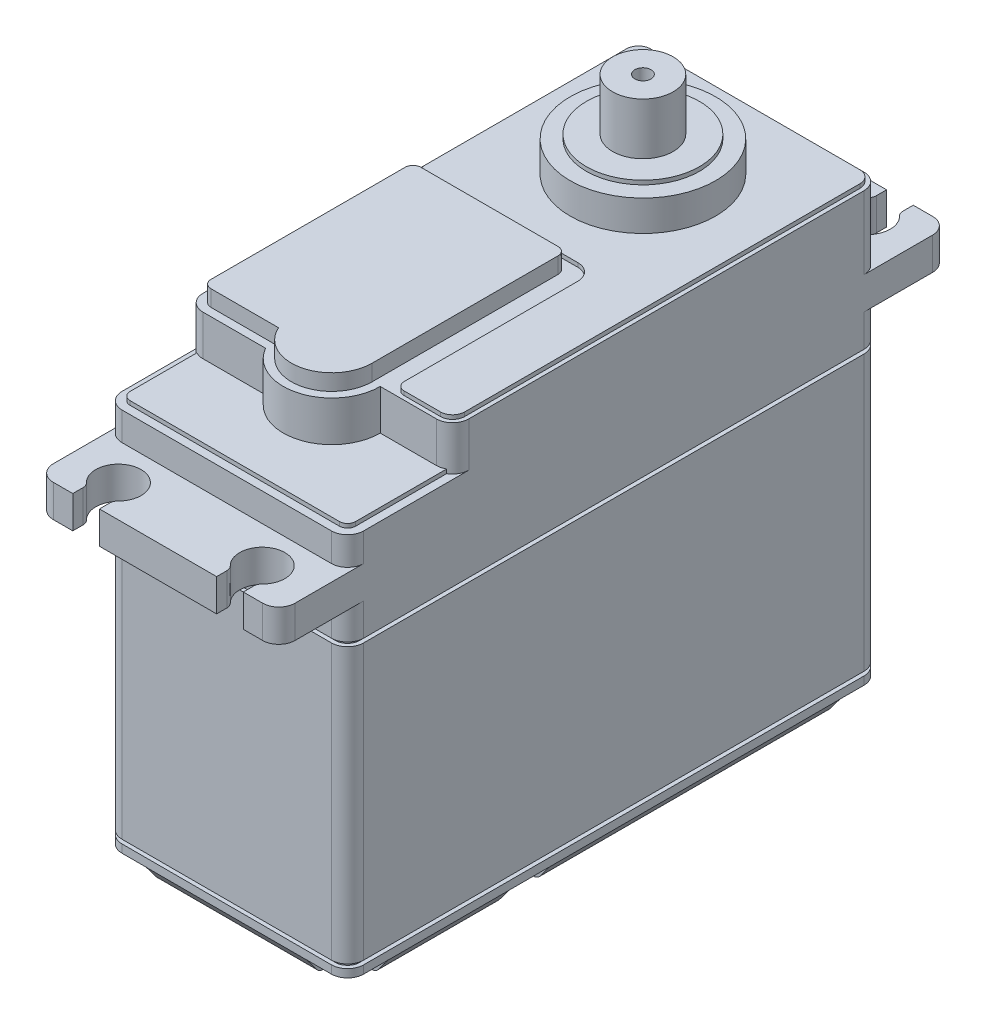
SolidWorks part; units mm, degrees
ref_plane "Front Plane" through (0, 0, 0) normal (0, 0, 1) x (1, 0, 0)
ref_plane "Top Plane" through (0, 0, 0) normal (0, 1, 0) x (1, 0, 0)
ref_plane "Right Plane" through (0, 0, 0) normal (1, 0, 0) x (0, 0, -1)
sketch "Sketch1" plane through (0, 0, 0) normal (0, 1, 0) x (1, 0, 0)
  line L1 (12.95, 32.95) -> (-12.95, 32.95)
  line L2 (14.95, 30.95) -> (14.95, -30.95)
  line L3 (12.95, -32.95) -> (-12.95, -32.95)
  line L4 (-14.95, 30.95) -> (-14.95, -30.95)
  line L5 (14.95, 32.95) -> (-14.95, -32.95) construction
  line L6 (14.95, -32.95) -> (-14.95, 32.95) construction
  arc A0 (-12.95, 32.95) -> (-14.95, 30.95) centre (-12.95, 30.95) ccw
  arc A1 (12.95, 32.95) -> (14.95, 30.95) centre (12.95, 30.95) cw
  arc A2 (-12.95, -32.95) -> (-14.95, -30.95) centre (-12.95, -30.95) cw
  arc A3 (12.95, -32.95) -> (14.95, -30.95) centre (12.95, -30.95) ccw
  point P0 (0, 0)
  dimension "D3" = 2
  dimension "D1" = 29.9
  dimension "D2" = 65.9
extrude "Boss-Extrude1" add sketch "Sketch1" along normal blind 42
sketch "Sketch2" plane through (0, 0, 0) normal (0, -1, 0) x (1, 0, 0)
  line L0 (-14.95, -27.95) -> (-14.95, -32.95)
  line L2 (-14.95, -32.95) -> (-9.95, -32.95)
  line L4 (-14.95, -27.95) -> (-12.45, -27.95)
  line L5 (-9.95, -30.45) -> (-9.95, -32.95)
  line L6 (14.95, 30.95) -> (14.95, -30.95) construction
  line L7 (-14.95, -30.95) -> (-14.95, 30.95) construction
  line L8 (9.95, -30.45) -> (9.95, -32.95)
  line L9 (14.95, -27.95) -> (12.45, -27.95)
  line L10 (14.95, -32.95) -> (9.95, -32.95)
  line L11 (14.95, -27.95) -> (14.95, -32.95)
  line L12 (14.95, 27.95) -> (14.95, 32.95)
  line L13 (14.95, 32.95) -> (9.95, 32.95)
  line L14 (14.95, 27.95) -> (12.45, 27.95)
  line L15 (9.95, 30.45) -> (9.95, 32.95)
  line L16 (-9.95, 30.45) -> (-9.95, 32.95)
  line L17 (-14.95, 27.95) -> (-12.45, 27.95)
  line L18 (-14.95, 32.95) -> (-9.95, 32.95)
  line L19 (-14.95, 27.95) -> (-14.95, 32.95)
  line L20 (-12.95, 32.95) -> (12.95, 32.95) construction
  line L21 (-12.45, -5.45) -> (-14.95, -5.45)
  line L22 (-14.95, -5.45) -> (-14.95, -10.45)
  line L23 (-14.95, -10.45) -> (-12.45, -10.45)
  line L24 (12.45, 7.95) -> (14.95, 7.95)
  line L25 (14.95, 7.95) -> (14.95, 12.95)
  line L26 (14.95, 12.95) -> (12.45, 12.95)
  arc A0 (-9.95, -30.45) -> (-12.45, -27.95) centre (-12.45, -30.45) ccw
  arc A1 (9.95, -30.45) -> (12.45, -27.95) centre (12.45, -30.45) cw
  arc A2 (9.95, 30.45) -> (12.45, 27.95) centre (12.45, 30.45) ccw
  arc A3 (-9.95, 30.45) -> (-12.45, 27.95) centre (-12.45, 30.45) cw
  arc A4 (12.45, 12.95) -> (12.45, 7.95) centre (12.45, 10.45) ccw
  arc A5 (-12.45, -10.45) -> (-12.45, -5.45) centre (-12.45, -7.95) ccw
  point P7 (-9.95, -32.95)
  point P8 (-14.95, -27.95)
  point P10 (14.95, 10.45)
  point P13 (-14.95, -7.95)
  point P18 (14.95, -27.95)
  point P19 (9.95, -32.95)
  point P32 (9.95, 32.95)
  point P33 (14.95, 27.95)
  point P34 (-14.95, 27.95)
  point P35 (-9.95, 32.95)
  dimension "D1" = 5
  dimension "D2" = 5
  dimension "D3" = 25
  dimension "D4" = 22.5
  dimension "D5" = 0
extrude "Cut-Extrude1" cut sketch "Sketch2" against normal blind 2
chamfer "Chamfer1" distance 1.5 angle 53 6 edges at (0, 0, 32.95) (-14.95, 0, 11.25) (-14.95, 0, -19.2) (0, 0, -32.95) (14.95, 0, 20.45) (14.95, 0, -10)
fillet "Fillet1" radius 1 6 edges at (13.45, 0, 20.45) (13.45, 0, -10) (0, 0, -31.45) (-13.45, 0, -19.2) (-13.45, 0, 11.25) (0, 0, 31.45)
sketch "Sketch3" plane through (0, 2, 0) normal (0, -1, 0) x (1, 0, 0)
  circle A0 centre (12.45, 30.45) radius 1.5
  circle A1 centre (12.45, 10.45) radius 1.5
  circle A2 centre (12.45, -30.45) radius 1.5
  circle A3 centre (-12.45, -30.45) radius 1.5
  circle A4 centre (-12.45, -8.1512) radius 1.5
  circle A5 centre (-12.45, 30.45) radius 1.5
extrude "Boss-Extrude2" add sketch "Sketch3" along normal blind 1
fillet "Fillet2" radius 0.3 6 edges at (12.45, 1, 28.95) (12.45, 1, 8.95) (12.45, 1, -31.95) (-12.45, 1, -31.95) (-12.45, 1, -9.6512) (-12.45, 1, 28.95)
sketch "Sketch4" plane through (0, 1, 0) normal (0, -1, 0) x (-1, 0, 0)
  line L0 (-12.1, -10.2) -> (-11.1743, -10.2)
  line L1 (-12.1, -30.2) -> (-11.1743, -30.2)
  line L2 (-12.7, -31.7257) -> (-12.7, -30.8)
  line L3 (-13.7257, -30.2) -> (-12.8, -30.2)
  line L4 (-12.2, -31.7257) -> (-12.2, -30.8)
  line L5 (-13.7257, -30.7) -> (-12.8, -30.7)
  line L6 (-12.1, -30.7) -> (-11.1743, -30.7)
  line L7 (-12.7, -30.1) -> (-12.7, -29.1743)
  line L9 (-12.2, 30.1) -> (-12.2, 29.1743)
  line L10 (-12.2, -30.1) -> (-12.2, -29.1743)
  line L11 (-12.7, 30.1) -> (-12.7, 29.1743)
  line L12 (-12.1, 30.7) -> (-11.1743, 30.7)
  line L13 (-13.7257, 30.7) -> (-12.8, 30.7)
  line L14 (-12.2, 31.7257) -> (-12.2, 30.8)
  line L15 (-13.7257, 30.2) -> (-12.8, 30.2)
  line L16 (-12.7, 31.7257) -> (-12.7, 30.8)
  line L17 (-12.1, 30.2) -> (-11.1743, 30.2)
  line L18 (12.1, 30.2) -> (11.1743, 30.2)
  line L19 (12.7, 31.7257) -> (12.7, 30.8)
  line L20 (13.7257, 30.2) -> (12.8, 30.2)
  line L21 (12.2, 31.7257) -> (12.2, 30.8)
  line L22 (13.7257, 30.7) -> (12.8, 30.7)
  line L23 (12.1, 30.7) -> (11.1743, 30.7)
  line L24 (12.7, 30.1) -> (12.7, 29.1743)
  line L25 (12.2, -30.1) -> (12.2, -29.1743)
  line L26 (12.2, 30.1) -> (12.2, 29.1743)
  line L27 (12.7, -30.1) -> (12.7, -29.1743)
  line L28 (12.1, -30.7) -> (11.1743, -30.7)
  line L29 (13.7257, -30.7) -> (12.8, -30.7)
  line L30 (12.2, -31.7257) -> (12.2, -30.8)
  line L31 (13.7257, -30.2) -> (12.8, -30.2)
  line L32 (12.7, -31.7257) -> (12.7, -30.8)
  line L33 (12.1, -30.2) -> (11.1743, -30.2)
  line L34 (-12.2, -10.1) -> (-12.2, -9.1743)
  line L35 (11.1743, 7.9012) -> (12.1, 7.9012)
  line L36 (12.2, 8.5012) -> (12.2, 9.4269)
  line L37 (12.7, 6.8754) -> (12.7, 7.8012)
  line L38 (-12.2, -11.7257) -> (-12.2, -10.8)
  line L39 (-13.7257, -10.7) -> (-12.8, -10.7)
  line L40 (11.1743, 8.4012) -> (12.1, 8.4012)
  line L41 (12.2, 6.8754) -> (12.2, 7.8012)
  line L42 (-12.7, -11.7257) -> (-12.7, -10.8)
  line L43 (-13.7257, -10.2) -> (-12.8, -10.2)
  line L44 (-12.7, -10.1) -> (-12.7, -9.1743)
  line L45 (12.8, 7.9012) -> (13.7257, 7.9012)
  line L47 (12.8, 8.4012) -> (13.7257, 8.4012)
  line L48 (12.7, 8.5012) -> (12.7, 9.4269)
  line L51 (-12.1, -10.7) -> (-11.15, -10.7)
  arc A1 (-12.7, -31.7257) -> (-12.2, -31.7257) centre (-12.45, -30.45) ccw
  arc A2 (-13.7257, -30.2) -> (-13.7257, -30.7) centre (-12.45, -30.45) ccw
  arc A3 (-12.2, -29.1743) -> (-12.7, -29.1743) centre (-12.45, -30.45) ccw
  arc A4 (-11.1743, -30.7) -> (-11.1743, -30.2) centre (-12.45, -30.45) ccw
  arc A5 (-12.1, -30.7) -> (-12.2, -30.8) centre (-12.1, -30.8) ccw
  arc A6 (-12.2, -30.1) -> (-12.1, -30.2) centre (-12.1, -30.1) ccw
  arc A7 (-12.8, -30.2) -> (-12.7, -30.1) centre (-12.8, -30.1) ccw
  arc A8 (-12.8, -30.7) -> (-12.7, -30.8) centre (-12.8, -30.8) cw
  arc A9 (-12.8, 30.7) -> (-12.7, 30.8) centre (-12.8, 30.8) ccw
  arc A10 (-12.8, 30.2) -> (-12.7, 30.1) centre (-12.8, 30.1) cw
  arc A11 (-12.2, 30.1) -> (-12.1, 30.2) centre (-12.1, 30.1) cw
  arc A12 (-12.1, 30.7) -> (-12.2, 30.8) centre (-12.1, 30.8) cw
  arc A13 (-11.1743, 30.7) -> (-11.1743, 30.2) centre (-12.45, 30.45) cw
  arc A14 (-12.2, 29.1743) -> (-12.7, 29.1743) centre (-12.45, 30.45) cw
  arc A15 (-13.7257, 30.2) -> (-13.7257, 30.7) centre (-12.45, 30.45) cw
  arc A16 (-12.7, 31.7257) -> (-12.2, 31.7257) centre (-12.45, 30.45) cw
  arc A17 (12.7, 31.7257) -> (12.2, 31.7257) centre (12.45, 30.45) ccw
  arc A18 (13.7257, 30.2) -> (13.7257, 30.7) centre (12.45, 30.45) ccw
  arc A19 (12.2, 29.1743) -> (12.7, 29.1743) centre (12.45, 30.45) ccw
  arc A20 (11.1743, 30.7) -> (11.1743, 30.2) centre (12.45, 30.45) ccw
  arc A21 (12.1, 30.7) -> (12.2, 30.8) centre (12.1, 30.8) ccw
  arc A22 (12.2, 30.1) -> (12.1, 30.2) centre (12.1, 30.1) ccw
  arc A23 (12.8, 30.2) -> (12.7, 30.1) centre (12.8, 30.1) ccw
  arc A24 (12.8, 30.7) -> (12.7, 30.8) centre (12.8, 30.8) cw
  arc A25 (12.8, -30.7) -> (12.7, -30.8) centre (12.8, -30.8) ccw
  arc A26 (12.8, -30.2) -> (12.7, -30.1) centre (12.8, -30.1) cw
  arc A27 (12.2, -30.1) -> (12.1, -30.2) centre (12.1, -30.1) cw
  arc A28 (12.1, -30.7) -> (12.2, -30.8) centre (12.1, -30.8) cw
  arc A29 (11.1743, -30.7) -> (11.1743, -30.2) centre (12.45, -30.45) cw
  arc A30 (12.2, -29.1743) -> (12.7, -29.1743) centre (12.45, -30.45) cw
  arc A31 (13.7257, -30.2) -> (13.7257, -30.7) centre (12.45, -30.45) cw
  arc A32 (12.7, -31.7257) -> (12.2, -31.7257) centre (12.45, -30.45) cw
  arc A33 (-12.7, -11.7257) -> (-12.2, -11.7257) centre (-12.45, -10.45) ccw
  arc A34 (12.2, 6.8754) -> (12.7, 6.8754) centre (12.45, 8.1512) ccw
  arc A35 (-13.7257, -10.2) -> (-13.7257, -10.7) centre (-12.45, -10.45) ccw
  arc A36 (-12.2, -9.1743) -> (-12.7, -9.1743) centre (-12.45, -10.45) ccw
  arc A37 (-11.1743, -10.7) -> (-11.1743, -10.2) centre (-12.45, -10.45) ccw
  arc A38 (-12.7, -10.1) -> (-12.8, -10.2) centre (-12.8, -10.1) cw
  arc A39 (-12.1, -10.2) -> (-12.2, -10.1) centre (-12.1, -10.1) cw
  arc A40 (-12.1, -10.7) -> (-12.2, -10.8) centre (-12.1, -10.8) ccw
  arc A41 (-12.7, -10.8) -> (-12.8, -10.7) centre (-12.8, -10.8) ccw
  arc A42 (13.7257, 7.9012) -> (13.7257, 8.4012) centre (12.45, 8.1512) ccw
  arc A43 (12.7, 9.4269) -> (12.2, 9.4269) centre (12.45, 8.1512) ccw
  arc A44 (11.1743, 8.4012) -> (11.1743, 7.9012) centre (12.45, 8.1512) ccw
  arc A45 (12.7, 8.5012) -> (12.8, 8.4012) centre (12.8, 8.5012) ccw
  arc A46 (12.8, 7.9012) -> (12.7, 7.8012) centre (12.8, 7.8012) ccw
  arc A47 (12.2, 8.5012) -> (12.1, 8.4012) centre (12.1, 8.5012) cw
  arc A48 (12.1, 7.9012) -> (12.2, 7.8012) centre (12.1, 7.8012) cw
  point P0 (-13.75, -30.45)
  point P1 (-11.15, -30.45)
  point P5 (-12.45, -31.75)
  point P6 (-12.45, -29.15)
  point P11 (-13.75, -30.2)
  point P12 (-11.15, -30.2)
  point P13 (-12.2, -31.75)
  point P14 (-12.2, -29.15)
  point P15 (-13.75, -30.7)
  point P16 (-11.15, -30.7)
  point P30 (-12.2, -30.2)
  point P33 (-12.7, -30.2)
  point P39 (-13.75, -10.45)
  point P61 (-12.7, 30.2)
  point P62 (-12.2, 30.2)
  point P105 (12.2, 30.2)
  point P106 (12.7, 30.2)
  point P107 (12.7, -30.2)
  point P108 (12.2, -30.2)
  point P110 (-11.15, -10.45)
  point P111 (-12.45, -9.15)
  point P112 (-12.45, -11.75)
  point P116 (12.45, 6.8512)
  point P117 (12.45, 9.4512)
  point P118 (13.75, 8.1512)
  point P119 (11.15, 8.1512)
  point P120 (11.15, 7.9012)
  point P121 (13.75, 7.9012)
  point P122 (12.7, 6.8512)
  point P123 (12.7, 9.4512)
  point P124 (-12.2, -11.75)
  point P125 (-12.2, -9.15)
  point P126 (-13.75, -10.7)
  point P130 (12.2, 6.8512)
  point P131 (12.2, 9.4512)
  point P132 (-12.7, -11.75)
  point P133 (-12.7, -9.15)
  point P134 (-13.75, -10.2)
  point P135 (-11.15, -10.2)
  point P145 (-12.2, -10.2)
  point P163 (12.7, 8.4012)
  circle M64 centre (-12.45, -30.45) radius 1.2
  dimension "D1" = 0.1
  dimension "D4" = 0.1
  dimension "D2" = 0.1
extrude "Cut-Extrude2" cut sketch "Sketch4" against normal blind 0.5 contours A32 L32 A25 L29 A31 L31 A26 L27 A30 L25 A27 L33 A29 L28 A28 L30 | L35 A48 L41 A34 L37 A46 L45 A42 L47 A45 L48 A43 L36 A47 L40 A44 | L22 A24 L19 A17 L21 A21 L23 A20 L18 A22 L26 A19 L24 A23 L20 A18 | A16 L16 A9 L13 A15 L15 A10 L11 A14 L9 A11 L17 A13 L12 A12 L14 | A41 L42 A33 L38 A40 L51 A37 L0 A39 L34 A36 L44 A38 L43 A35 L39 | L5 A8 L2 L4 A5 L6 L1 A6 L10 L7 A7 L3 M64
ref_plane "Plane1" through (0, 3, 0) normal (0, -1, 0) x (-1, 0, 0)
sketch "Sketch5" plane through (0, 3, 0) normal (0, -1, 0) x (-1, 0, 0)
  line L0 (-14.95, -30.95) -> (-14.95, 30.95)
  line L1 (-12.95, 32.95) -> (12.95, 32.95)
  line L2 (14.95, 30.95) -> (14.95, -30.95)
  line L3 (12.95, -32.95) -> (-12.95, -32.95)
  line L4 (12.95, -32.45) -> (-12.95, -32.45)
  line L5 (-14.45, -30.95) -> (-14.45, 30.95)
  line L6 (-12.95, 32.45) -> (12.95, 32.45)
  line L7 (14.45, 30.95) -> (14.45, -30.95)
  line L181 (-14.95, -7.95) -> (-14.95, -12.95)
  line L182 (-14.95, 27.95) -> (-14.95, -7.95)
  line L183 (-14.95, 30.95) -> (-14.95, 27.95)
  line L184 (-9.95, 32.95) -> (-12.95, 32.95)
  line L185 (9.95, 32.95) -> (-9.95, 32.95)
  line L186 (12.95, 32.95) -> (9.95, 32.95)
  line L187 (14.95, 27.95) -> (14.95, 30.95)
  line L188 (14.95, 10.45) -> (14.95, 27.95)
  line L189 (14.95, 5.45) -> (14.95, 10.45)
  line L190 (14.95, -27.95) -> (14.95, 5.45)
  line L191 (14.95, -30.95) -> (14.95, -27.95)
  line L192 (9.95, -32.95) -> (12.95, -32.95)
  line L193 (-9.95, -32.95) -> (9.95, -32.95)
  line L194 (-12.95, -32.95) -> (-9.95, -32.95)
  line L195 (-14.95, -27.95) -> (-14.95, -30.95)
  line L196 (-14.95, -12.95) -> (-14.95, -27.95)
  arc A0 (-14.45, -30.95) -> (-12.95, -32.45) centre (-12.95, -30.95) ccw
  arc A1 (-12.95, 32.45) -> (-14.45, 30.95) centre (-12.95, 30.95) ccw
  arc A2 (14.45, 30.95) -> (12.95, 32.45) centre (12.95, 30.95) ccw
  arc A3 (12.95, -32.45) -> (14.45, -30.95) centre (12.95, -30.95) ccw
  arc A49 (-12.95, 32.95) -> (-14.95, 30.95) centre (-12.95, 30.95) ccw
  arc A50 (14.95, 30.95) -> (12.95, 32.95) centre (12.95, 30.95) ccw
  arc A51 (12.95, -32.95) -> (14.95, -30.95) centre (12.95, -30.95) ccw
  arc A52 (-14.95, -30.95) -> (-12.95, -32.95) centre (-12.95, -30.95) ccw
  arc A53 (-12.95, 32.95) -> (-14.95, 30.95) centre (-12.95, 30.95) ccw
  arc A54 (14.95, 30.95) -> (12.95, 32.95) centre (12.95, 30.95) ccw
  arc A55 (12.95, -32.95) -> (14.95, -30.95) centre (12.95, -30.95) ccw
  arc A56 (-14.95, -30.95) -> (-12.95, -32.95) centre (-12.95, -30.95) ccw
  dimension "D1" = 0
  dimension "D2" = 0.5
extrude "Cut-Extrude3" cut sketch "Sketch5" against normal blind 0.5
ref_plane "Plane2" through (0, 38, 0) normal (0, 1, 0) x (1, 0, 0)
sketch "Sketch6" plane through (0, 38, 0) normal (0, 1, 0) x (1, 0, 0)
  line L8 (-14.45, 30.95) -> (-14.45, -30.95)
  line L9 (-12.95, -32.45) -> (12.95, -32.45)
  line L10 (14.45, -30.95) -> (14.45, 30.95)
  line L11 (12.95, 32.45) -> (-12.95, 32.45)
  line L12 (-14.45, 30.95) -> (-14.45, -30.95)
  line L13 (-12.95, -32.45) -> (12.95, -32.45)
  line L14 (14.45, -30.95) -> (14.45, 30.95)
  line L15 (12.95, 32.45) -> (-12.95, 32.45)
  line L20 (-14.95, 30.95) -> (-14.95, -30.95)
  line L21 (-12.95, -32.95) -> (12.95, -32.95)
  line L22 (14.95, -30.95) -> (14.95, 30.95)
  line L23 (12.95, 32.95) -> (-12.95, 32.95)
  line L24 (-14.95, 30.95) -> (-14.95, -30.95)
  line L25 (-12.95, -32.95) -> (12.95, -32.95)
  line L26 (14.95, -30.95) -> (14.95, 30.95)
  line L27 (12.95, 32.95) -> (-12.95, 32.95)
  arc A8 (-12.95, 32.45) -> (-14.45, 30.95) centre (-12.95, 30.95) ccw
  arc A9 (-14.45, -30.95) -> (-12.95, -32.45) centre (-12.95, -30.95) ccw
  arc A10 (12.95, -32.45) -> (14.45, -30.95) centre (12.95, -30.95) ccw
  arc A11 (14.45, 30.95) -> (12.95, 32.45) centre (12.95, 30.95) ccw
  arc A12 (-12.95, 32.45) -> (-14.45, 30.95) centre (-12.95, 30.95) ccw
  arc A13 (-14.45, -30.95) -> (-12.95, -32.45) centre (-12.95, -30.95) ccw
  arc A14 (12.95, -32.45) -> (14.45, -30.95) centre (12.95, -30.95) ccw
  arc A15 (14.45, 30.95) -> (12.95, 32.45) centre (12.95, 30.95) ccw
  arc A20 (-12.95, 32.95) -> (-14.95, 30.95) centre (-12.95, 30.95) ccw
  arc A21 (-14.95, -30.95) -> (-12.95, -32.95) centre (-12.95, -30.95) ccw
  arc A22 (12.95, -32.95) -> (14.95, -30.95) centre (12.95, -30.95) ccw
  arc A23 (14.95, 30.95) -> (12.95, 32.95) centre (12.95, 30.95) ccw
  arc A24 (-12.95, 32.95) -> (-14.95, 30.95) centre (-12.95, 30.95) ccw
  arc A25 (-14.95, -30.95) -> (-12.95, -32.95) centre (-12.95, -30.95) ccw
  arc A26 (12.95, -32.95) -> (14.95, -30.95) centre (12.95, -30.95) ccw
  arc A27 (14.95, 30.95) -> (12.95, 32.95) centre (12.95, 30.95) ccw
  dimension "D1" = 0.5
  dimension "D2" = 0
extrude "Cut-Extrude4" cut sketch "Sketch6" against normal blind 0.5
sketch "Sketch7" plane through (0, 42, 0) normal (0, 1, 0) x (1, 0, 0)
  line L0 (7.25, 41.45) -> (-7.25, 41.45)
  line L3 (10.55, 40.1735) -> (10.55, 41.45)
  line L4 (7.25, 40.1735) -> (7.25, 41.45)
  line L5 (12.95, 41.45) -> (10.55, 41.45)
  line L6 (14.95, 39.45) -> (14.95, -39.45)
  line L7 (12.95, -41.45) -> (10.55, -41.45)
  line L8 (-14.95, 39.45) -> (-14.95, -39.45)
  line L9 (7.25, -41.45) -> (-7.25, -41.45)
  line L10 (-10.55, -41.45) -> (-12.95, -41.45)
  line L11 (-7.25, 40.1735) -> (-7.25, 41.45)
  line L12 (-10.55, 40.1735) -> (-10.55, 41.45)
  line L13 (-10.55, -40.1735) -> (-10.55, -41.45)
  line L14 (-7.25, -40.1735) -> (-7.25, -41.45)
  line L15 (7.25, -40.1735) -> (7.25, -41.45)
  line L16 (10.55, -40.1735) -> (10.55, -41.45)
  line L17 (-10.55, 41.45) -> (-12.95, 41.45)
  arc A0 (-10.8526, 39.4568) -> (-6.9474, 39.4568) centre (-8.9, 37.45) ccw
  arc A1 (6.9474, 39.4568) -> (10.8526, 39.4568) centre (8.9, 37.45) ccw
  arc A2 (10.8526, -39.4568) -> (6.9474, -39.4568) centre (8.9, -37.45) ccw
  arc A3 (-6.9474, -39.4568) -> (-10.8526, -39.4568) centre (-8.9, -37.45) ccw
  arc A4 (-12.95, 41.45) -> (-14.95, 39.45) centre (-12.95, 39.45) ccw
  arc A5 (12.95, 41.45) -> (14.95, 39.45) centre (12.95, 39.45) cw
  arc A6 (-12.95, -41.45) -> (-14.95, -39.45) centre (-12.95, -39.45) cw
  arc A7 (14.95, -39.45) -> (12.95, -41.45) centre (12.95, -39.45) cw
  arc A8 (10.55, -40.1735) -> (10.8526, -39.4568) centre (11.55, -40.1735) cw
  arc A9 (7.25, -40.1735) -> (6.9474, -39.4568) centre (6.25, -40.1735) ccw
  arc A10 (-7.25, -40.1735) -> (-6.9474, -39.4568) centre (-6.25, -40.1735) cw
  arc A11 (-10.55, -40.1735) -> (-10.8526, -39.4568) centre (-11.55, -40.1735) ccw
  arc A12 (-10.55, 40.1735) -> (-10.8526, 39.4568) centre (-11.55, 40.1735) cw
  arc A13 (-7.25, 40.1735) -> (-6.9474, 39.4568) centre (-6.25, 40.1735) ccw
  arc A14 (7.25, 40.1735) -> (6.9474, 39.4568) centre (6.25, 40.1735) cw
  arc A15 (10.55, 40.1735) -> (10.8526, 39.4568) centre (11.55, 40.1735) ccw
  point P1 (10.55, 37.45)
  point P2 (8.9, 44.4881)
  point P3 (0, 0)
  point P7 (10.55, 44.4881)
  point P8 (7.25, 37.45)
  point P10 (0, 0)
  point P14 (-8.9, 0)
  point P22 (7.25, 44.4881)
  dimension "D1" = 5.6
  dimension "D2" = 2
  dimension "D3" = 1
extrude "Boss-Extrude3" add sketch "Sketch7" along normal blind 4
sketch "Sketch8" plane through (0, 46, 0) normal (0, 1, 0) x (1, 0, 0)
  line L0 (-14.95, 39.45) -> (-14.95, 30.95) construction
  line L1 (-12.95, 32.95) -> (12.95, 32.95)
  line L2 (-14.95, 30.95) -> (-14.95, -30.95)
  line L3 (-12.95, -32.95) -> (12.95, -32.95)
  line L4 (14.95, 30.95) -> (14.95, -30.95)
  line L5 (14.95, -39.45) -> (14.95, -30.95) construction
  arc A0 (-14.95, -30.95) -> (-12.95, -32.95) centre (-12.95, -30.95) ccw
  arc A1 (12.95, -32.95) -> (14.95, -30.95) centre (12.95, -30.95) ccw
  arc A2 (12.95, 32.95) -> (14.95, 30.95) centre (12.95, 30.95) cw
  arc A3 (-12.95, 32.95) -> (-14.95, 30.95) centre (-12.95, 30.95) ccw
  point P12 (14.95, -32.95)
  point P17 (-14.95, 32.95)
  dimension "D1" = 2
extrude "Boss-Extrude4" add sketch "Sketch8" along normal blind 4
sketch "Sketch9" plane through (0, 50, 0) normal (0, 1, 0) x (1, 0, 0)
  line L4 (-12.95, -32.95) -> (12.95, -32.95)
  line L5 (14.95, -30.95) -> (14.95, 30.95)
  line L6 (12.95, 32.95) -> (-12.95, 32.95)
  line L7 (-14.95, 30.95) -> (-14.95, -30.95)
  line L8 (-12.95, -31.95) -> (12.95, -31.95)
  line L9 (13.95, -30.95) -> (13.95, 30.95)
  line L10 (12.95, 31.95) -> (-12.95, 31.95)
  line L11 (-13.95, 30.95) -> (-13.95, -30.95)
  line L12 (-12.95, -31.95) -> (12.95, -31.95)
  line L13 (13.95, -30.95) -> (13.95, 30.95)
  line L14 (12.95, 31.95) -> (-12.95, 31.95)
  line L15 (-13.95, 30.95) -> (-13.95, -30.95)
  arc A4 (-14.95, -30.95) -> (-12.95, -32.95) centre (-12.95, -30.95) ccw
  arc A5 (12.95, -32.95) -> (14.95, -30.95) centre (12.95, -30.95) ccw
  arc A6 (14.95, 30.95) -> (12.95, 32.95) centre (12.95, 30.95) ccw
  arc A7 (-12.95, 32.95) -> (-14.95, 30.95) centre (-12.95, 30.95) ccw
  arc A8 (-13.95, -30.95) -> (-12.95, -31.95) centre (-12.95, -30.95) ccw
  arc A9 (12.95, -31.95) -> (13.95, -30.95) centre (12.95, -30.95) ccw
  arc A10 (13.95, 30.95) -> (12.95, 31.95) centre (12.95, 30.95) ccw
  arc A11 (-12.95, 31.95) -> (-13.95, 30.95) centre (-12.95, 30.95) ccw
  arc A12 (-13.95, -30.95) -> (-12.95, -31.95) centre (-12.95, -30.95) ccw
  arc A13 (12.95, -31.95) -> (13.95, -30.95) centre (12.95, -30.95) ccw
  arc A14 (13.95, 30.95) -> (12.95, 31.95) centre (12.95, 30.95) ccw
  arc A15 (-12.95, 31.95) -> (-13.95, 30.95) centre (-12.95, 30.95) ccw
  dimension "D1" = 1
  dimension "D2" = 1
extrude "Cut-Extrude5" cut sketch "Sketch9" against normal blind 0.5
sketch "Sketch10" plane through (0, 50, 0) normal (0, 1, 0) x (1, 0, 0)
  line L0 (14.95, 30.95) -> (14.95, 39.45) construction
  line L1 (12.95, -19.95) -> (6, -19.95)
  line L3 (12.95, 32.95) -> (-12.95, 32.95)
  line L5 (14.95, -30.95) -> (14.95, 30.95) construction
  line L7 (14.95, 30.95) -> (14.95, -17.95)
  line L10 (-12.95, -22.95) -> (-5.1962, -22.95)
  line L11 (-14.95, 30.95) -> (-14.95, -30.95) construction
  line L12 (-14.95, 30.95) -> (-14.95, -20.95)
  arc A0 (-5.1962, -22.95) -> (6, -19.95) centre (0, -19.95) ccw
  arc A1 (12.95, -19.95) -> (14.95, -17.95) centre (12.95, -17.95) ccw
  arc A2 (-12.95, -22.95) -> (-14.95, -20.95) centre (-12.95, -20.95) cw
  arc A3 (-12.95, 32.95) -> (-14.95, 30.95) centre (-12.95, 30.95) ccw
  arc A4 (12.95, 32.95) -> (14.95, 30.95) centre (12.95, 30.95) cw
  point P16 (14.95, -19.95)
  point P19 (-14.95, -22.95)
  point P26 (14.95, 32.95)
  dimension "D3" = 12
  dimension "D1" = 2
extrude "Boss-Extrude5" add sketch "Sketch10" along normal blind 5 and the other way blind 2.5
sketch "Sketch11" plane through (0, 55, 0) normal (0, 1, 0) x (1, 0, 0)
  line L5 (5, -19.95) -> (5, 3.05)
  line L6 (4, 4.05) -> (-12.95, 4.05)
  line L10 (4.899, -18.95) -> (12.95, -18.95)
  line L11 (13.95, -17.95) -> (13.95, 30.95)
  line L12 (12.95, 31.95) -> (-12.95, 31.95)
  line L13 (-13.95, 30.95) -> (-13.95, -20.95)
  line L14 (-12.95, -21.95) -> (-4.5826, -21.95)
  line L18 (-13.95, 3.05) -> (-13.95, -20.95)
  line L19 (-12.95, -21.95) -> (-4.5826, -21.95)
  arc A5 (4, 4.05) -> (5, 3.05) centre (4, 3.05) cw
  arc A6 (-12.95, 4.05) -> (-13.95, 3.05) centre (-12.95, 3.05) ccw
  arc A10 (-4.5826, -21.95) -> (4.899, -18.95) centre (0, -19.95) ccw
  arc A11 (12.95, -18.95) -> (13.95, -17.95) centre (12.95, -17.95) ccw
  arc A12 (13.95, 30.95) -> (12.95, 31.95) centre (12.95, 30.95) ccw
  arc A13 (-12.95, 31.95) -> (-13.95, 30.95) centre (-12.95, 30.95) ccw
  arc A14 (-13.95, -20.95) -> (-12.95, -21.95) centre (-12.95, -20.95) ccw
  arc A15 (-4.5826, -21.95) -> (5, -19.95) centre (0, -19.95) ccw
  arc A19 (-13.95, -20.95) -> (-12.95, -21.95) centre (-12.95, -20.95) ccw
  point P0 (-13.95, 4.05)
  point P8 (-13.95, 4.05)
  dimension "D3" = 1
  dimension "D2" = 26
  dimension "D1" = 1
extrude "Boss-Extrude6" add sketch "Sketch11" along normal blind 2
sketch "Sketch12" plane through (0, 55, 0) normal (0, 1, 0) x (1, 0, 0)
  line L5 (-4.475, 5.0228) -> (-4.475, 5.05)
  line L7 (7.45, -18.45) -> (7.45, 3.0454)
  line L8 (5.4454, 5.0454) -> (-13.4477, 5.0023)
  line L10 (5.4772, -19.45) -> (12.95, -19.45)
  line L11 (14.45, -17.95) -> (14.45, 30.95)
  line L12 (12.95, 32.45) -> (-12.95, 32.45)
  line L13 (-14.45, 30.95) -> (-14.45, -20.95)
  line L14 (-12.95, -22.45) -> (-4.899, -22.45)
  line L15 (8.45, -19.45) -> (12.95, -19.45)
  line L16 (14.45, -17.95) -> (14.45, 30.95)
  line L17 (12.95, 32.45) -> (-12.95, 32.45)
  line L18 (-14.45, 30.95) -> (-14.45, 6.0023)
  arc A5 (-13.4477, 5.0023) -> (-14.45, 6.0023) centre (-13.45, 6.0023) cw
  arc A6 (7.45, -18.45) -> (8.45, -19.45) centre (8.45, -18.45) ccw
  arc A7 (7.45, 3.0454) -> (5.4454, 5.0454) centre (5.45, 3.0454) ccw
  arc A10 (-4.899, -22.45) -> (5.4772, -19.45) centre (0, -19.95) ccw
  arc A11 (12.95, -19.45) -> (14.45, -17.95) centre (12.95, -17.95) ccw
  arc A12 (14.45, 30.95) -> (12.95, 32.45) centre (12.95, 30.95) ccw
  arc A13 (-12.95, 32.45) -> (-14.45, 30.95) centre (-12.95, 30.95) ccw
  arc A14 (-14.45, -20.95) -> (-12.95, -22.45) centre (-12.95, -20.95) ccw
  arc A16 (12.95, -19.45) -> (14.45, -17.95) centre (12.95, -17.95) ccw
  arc A17 (14.45, 30.95) -> (12.95, 32.45) centre (12.95, 30.95) ccw
  arc A18 (-12.95, 32.45) -> (-14.45, 30.95) centre (-12.95, 30.95) ccw
  point P0 (7.45, -17.95)
  dimension "D3" = 1
  dimension "D4" = 2
  dimension "D2" = 7
  dimension "D1" = 0.5
extrude "Boss-Extrude7" add sketch "Sketch12" along normal blind 0.5
sketch "Sketch13" plane through (0, 42, 0) normal (0, 1, 0) x (1, 0, 0)
  circle A1 centre (0, 18.55) radius 9
  dimension "D1" = 18
extrude "Boss-Extrude8" add sketch "Sketch13" along normal blind 17.3
sketch "Sketch14" plane through (0, 59.3, 0) normal (0, 1, 0) x (1, 0, 0)
  circle A0 centre (0, 18.55) radius 7
extrude "Boss-Extrude9" add sketch "Sketch14" along normal blind 0.5
sketch "Sketch15" plane through (0, 59.8, 0) normal (0, 1, 0) x (1, 0, 0)
  circle A0 centre (0, 18.55) radius 3.75
  dimension "D1" = 7.5
extrude "Boss-Extrude10" add sketch "Sketch15" along normal blind 6.4
sketch "Sketch16" plane through (0, 66.2, 0) normal (0, 1, 0) x (1, 0, 0)
  circle A0 centre (0, 18.55) radius 1
extrude "Cut-Extrude6" cut sketch "Sketch16" against normal blind 6.4
scale "Scale2" bodies to scale 116 scale about centroid uniform scaling yes scale factor 0.53076
